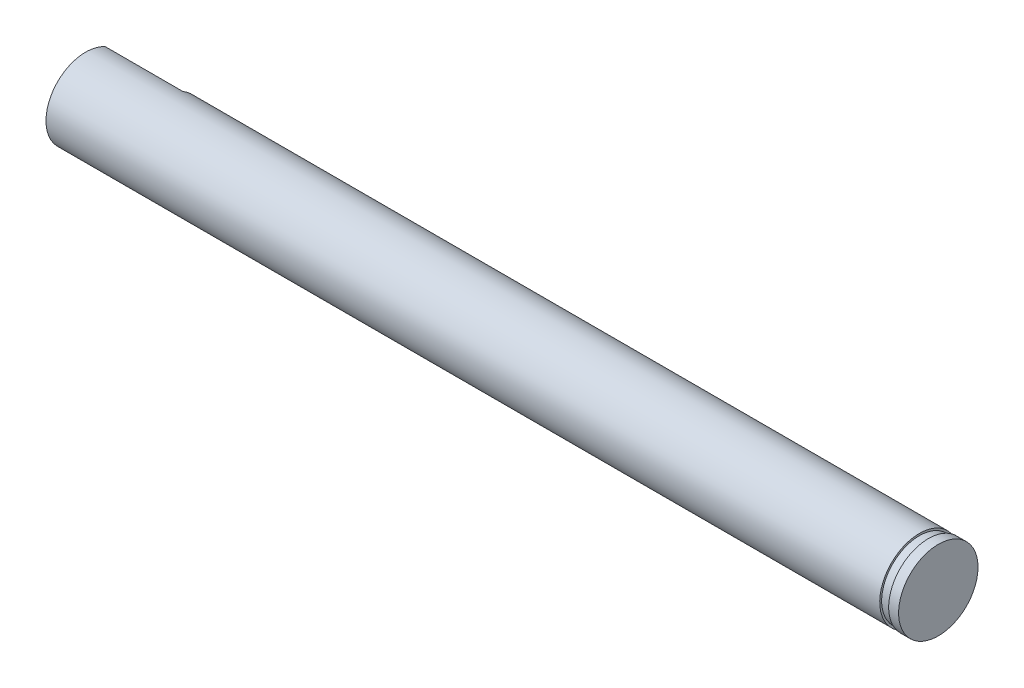
SolidWorks part; units mm, degrees
ref_plane "Front Plane" through (0, 0, 0) normal (0, 0, 1) x (1, 0, 0)
ref_plane "Top Plane" through (0, 0, 0) normal (0, 1, 0) x (1, 0, 0)
ref_plane "Right Plane" through (0, 0, 0) normal (1, 0, 0) x (0, 0, -1)
sketch "Sketch1" plane through (0, 0, 0) normal (1, 0, 0) x (0, 0, -1)
  line L0 (1.985, 3.467) -> (1.985, -3.467)
  line L1 (-3.995, -8) -> (1.985, -8) construction
  line L2 (-3.995, -8) -> (-3.995, 0) construction
  line L4 (1.985, -8) -> (1.985, 3.467) construction
  arc A0 (1.985, 3.467) -> (1.985, -3.467) centre (0, 0) ccw
  dimension "D1" = 7.99
  dimension "D2" = 5.98
  dimension "D3" = 8
extrude "Boss-Extrude1" add sketch "Sketch1" along normal blind 7.8
sketch "Sketch2" plane through (7.8, 0, 0) normal (1, 0, 0) x (0, 0, -1)
  circle A0 centre (0, 0) radius 3.995
  dimension "D1" = 7.99
extrude "Boss-Extrude2" add sketch "Sketch2" along normal blind 78
sketch "Sketch3" plane through (85.8, 0, 0) normal (1, 0, 0) x (0, 0, -1)
  circle A0 centre (0, 0) radius 3.8
  circle A1 centre (0, 0) radius 5
  dimension "D1" = 7.6
  dimension "D2" = 10
extrude "Cut-Extrude1" cut sketch "Sketch3" against normal blind 0.9 from offset 1 offset against normal yes
ref_plane "Plane1" through (0, 0, -3.995) normal (0, 0, -1) x (-1, 0, 0)
sketch "Sketch4" plane through (0, 0, -3.995) normal (0, 0, -1) x (-1, 0, 0)
  line L0 (0, 0) -> (-43.434, 0) construction
  circle A0 centre (-43.434, 0) radius 1.778
  dimension "D2" = 3.556
  dimension "D1" = 43.434
extrude "Cut-Extrude2" cut sketch "Sketch4" against normal blind 1.905 draft 45
